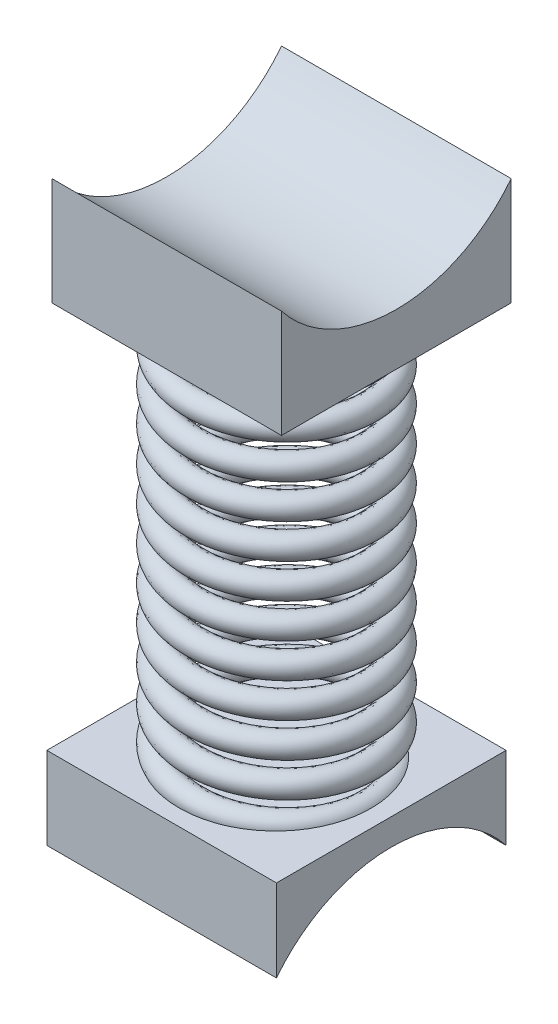
SolidWorks part; units mm, degrees
ref_plane "Front Plane" through (0, 0, 0) normal (0, 0, 1) x (1, 0, 0)
ref_plane "Top Plane" through (0, 0, 0) normal (0, 1, 0) x (1, 0, 0)
ref_plane "Right Plane" through (0, 0, 0) normal (1, 0, 0) x (0, 0, -1)
sketch "Sketch1" plane through (0, 0, 0) normal (0, 1, 0) x (1, 0, 0)
  circle A0 centre (0, 0) radius 7.62
curve "Helix/Spiral1" pitch 3 height 45 turns 15
sweep "Sweep1" add path "Helix/Spiral1" circular profile diameter 2 parameters "D3"=2
sketch "Sketch10" plane through (0, 0, 0) normal (0, 1, 0) x (1, 0, 0)
  line L1 (-10, 10) -> (10, 10)
  line L2 (-10, 10) -> (-10, -10)
  line L3 (-10, -10) -> (10, -10)
  line L4 (10, 10) -> (10, -10)
  line L5 (-10, 10) -> (10, -10) construction
  line L6 (-10, -10) -> (10, 10) construction
  point P0 (0, 0)
extrude "Boss-Extrude1" add sketch "Sketch10" along normal mid plane 10 contours L2 L1 L4 L3
sketch3d "3DSketch2"
  line L1 (-9.5584, 43.9677, -10) -> (10.4416, 43.9677, -10)
  line L2 (-9.5584, 43.9677, -10) -> (-9.5584, 43.9677, 10)
  line L3 (-9.5584, 43.9677, 10) -> (10.4416, 43.9677, 10)
  line L4 (10.4416, 43.9677, -10) -> (10.4416, 43.9677, 10)
  line L5 (-9.5584, 43.9677, -10) -> (10.4416, 43.9677, 10) construction
  line L6 (-9.5584, 43.9677, 10) -> (10.4416, 43.9677, -10) construction
  spline S0 degree 3 poles (-7.62, 0, 0) (-7.62, 0.0621, -0.9911) (-7.2232, 0.1877, -2.9949) (-5.5284, 0.375, -5.5277) (-2.992, 0.5625, -7.2234) (0, 0.75, -7.8183) (2.992, 0.9375, -7.2233) (5.5284, 1.125, -5.5284) (7.2232, 1.3125, -2.992) (7.8184, 1.5, 0) (7.2232, 1.6875, 2.992) (5.5284, 1.875, 5.5284) (2.992, 2.0625, 7.2232) (0, 2.25, 7.8184) (-2.992, 2.4375, 7.2232) (-5.5284, 2.625, 5.5284) (-7.2232, 2.8125, 2.992) (-7.8184, 3, 0) (-7.2232, 3.1875, -2.992) (-5.5284, 3.375, -5.5284) (-2.992, 3.5625, -7.2232) (0, 3.75, -7.8184) (2.992, 3.9375, -7.2232) (5.5284, 4.125, -5.5284) (7.2232, 4.3125, -2.992) (7.8184, 4.5, 0) (7.2232, 4.6875, 2.992) (5.5284, 4.875, 5.5284) (2.992, 5.0625, 7.2232) (0, 5.25, 7.8184) (-2.992, 5.4375, 7.2232) (-5.5284, 5.625, 5.5284) (-7.2232, 5.8125, 2.992) (-7.8184, 6, 0) (-7.2232, 6.1875, -2.992) (-5.5284, 6.375, -5.5284) (-2.992, 6.5625, -7.2232) (0, 6.75, -7.8184) (2.992, 6.9375, -7.2232) (5.5284, 7.125, -5.5284) (7.2232, 7.3125, -2.992) (7.8184, 7.5, 0) (7.2232, 7.6875, 2.992) (5.5284, 7.875, 5.5284) (2.992, 8.0625, 7.2232) (0, 8.25, 7.8184) (-2.992, 8.4375, 7.2232) (-5.5284, 8.625, 5.5284) (-7.2232, 8.8125, 2.992) (-7.8184, 9, 0) (-7.2232, 9.1875, -2.992) (-5.5284, 9.375, -5.5284) (-2.992, 9.5625, -7.2232) (0, 9.75, -7.8184) (2.992, 9.9375, -7.2232) (5.5284, 10.125, -5.5284) (7.2232, 10.3125, -2.992) (7.8184, 10.5, 0) (7.2232, 10.6875, 2.992) (5.5284, 10.875, 5.5284) (2.992, 11.0625, 7.2232) (0, 11.25, 7.8184) (-2.992, 11.4375, 7.2232) (-5.5284, 11.625, 5.5284) (-7.2232, 11.8125, 2.992) (-7.8184, 12, 0) (-7.2232, 12.1875, -2.992) (-5.5284, 12.375, -5.5284) (-2.992, 12.5625, -7.2232) (0, 12.75, -7.8184) (2.992, 12.9375, -7.2232) (5.5284, 13.125, -5.5284) (7.2232, 13.3125, -2.992) (7.8184, 13.5, 0) (7.2232, 13.6875, 2.992) (5.5284, 13.875, 5.5284) (2.992, 14.0625, 7.2232) (0, 14.25, 7.8184) (-2.992, 14.4375, 7.2232) (-5.5284, 14.625, 5.5284) (-7.2232, 14.8125, 2.992) (-7.8184, 15, 0) (-7.2232, 15.1875, -2.992) (-5.5284, 15.375, -5.5284) (-2.992, 15.5625, -7.2232) (0, 15.75, -7.8184) (2.992, 15.9375, -7.2232) (5.5284, 16.125, -5.5284) (7.2232, 16.3125, -2.992) (7.8184, 16.5, 0) (7.2232, 16.6875, 2.992) (5.5284, 16.875, 5.5284) (2.992, 17.0625, 7.2232) (0, 17.25, 7.8184) (-2.992, 17.4375, 7.2232) (-5.5284, 17.625, 5.5284) (-7.2232, 17.8125, 2.992) (-7.8184, 18, 0) (-7.2232, 18.1875, -2.992) (-5.5284, 18.375, -5.5284) (-2.992, 18.5625, -7.2232) (0, 18.75, -7.8184) (2.992, 18.9375, -7.2232) (5.5284, 19.125, -5.5284) (7.2232, 19.3125, -2.992) (7.8184, 19.5, 0) (7.2232, 19.6875, 2.992) (5.5284, 19.875, 5.5284) (2.992, 20.0625, 7.2232) (0, 20.25, 7.8184) (-2.992, 20.4375, 7.2232) (-5.5284, 20.625, 5.5284) (-7.2232, 20.8125, 2.992) (-7.8184, 21, 0) (-7.2232, 21.1875, -2.992) (-5.5284, 21.375, -5.5284) (-2.992, 21.5625, -7.2232) (0, 21.75, -7.8184) (2.992, 21.9375, -7.2232) (5.5284, 22.125, -5.5284) (7.2232, 22.3125, -2.992) (7.8184, 22.5, 0) (7.2232, 22.6875, 2.992) (5.5284, 22.875, 5.5284) (2.992, 23.0625, 7.2232) (0, 23.25, 7.8184) (-2.992, 23.4375, 7.2232) (-5.5284, 23.625, 5.5284) (-7.2232, 23.8125, 2.992) (-7.8184, 24, 0) (-7.2232, 24.1875, -2.992) (-5.5284, 24.375, -5.5284) (-2.992, 24.5625, -7.2232) (0, 24.75, -7.8184) (2.992, 24.9375, -7.2232) (5.5284, 25.125, -5.5284) (7.2232, 25.3125, -2.992) (7.8184, 25.5, 0) (7.2232, 25.6875, 2.992) (5.5284, 25.875, 5.5284) (2.992, 26.0625, 7.2232) (0, 26.25, 7.8184) (-2.992, 26.4375, 7.2232) (-5.5284, 26.625, 5.5284) (-7.2232, 26.8125, 2.992) (-7.8184, 27, 0) (-7.2232, 27.1875, -2.992) (-5.5284, 27.375, -5.5284) (-2.992, 27.5625, -7.2232) (0, 27.75, -7.8184) (2.992, 27.9375, -7.2232) (5.5284, 28.125, -5.5284) (7.2232, 28.3125, -2.992) (7.8184, 28.5, 0) (7.2232, 28.6875, 2.992) (5.5284, 28.875, 5.5284) (2.992, 29.0625, 7.2232) (0, 29.25, 7.8184) (-2.992, 29.4375, 7.2232) (-5.5284, 29.625, 5.5284) (-7.2232, 29.8125, 2.992) (-7.8184, 30, 0) (-7.2232, 30.1875, -2.992) (-5.5284, 30.375, -5.5284) (-2.992, 30.5625, -7.2232) (0, 30.75, -7.8184) (2.992, 30.9375, -7.2232) (5.5284, 31.125, -5.5284) (7.2232, 31.3125, -2.992) (7.8184, 31.5, 0) (7.2232, 31.6875, 2.992) (5.5284, 31.875, 5.5284) (2.992, 32.0625, 7.2232) (0, 32.25, 7.8184) (-2.992, 32.4375, 7.2232) (-5.5284, 32.625, 5.5284) (-7.2232, 32.8125, 2.992) (-7.8184, 33, 0) (-7.2232, 33.1875, -2.992) (-5.5284, 33.375, -5.5284) (-2.992, 33.5625, -7.2232) (0, 33.75, -7.8184) (2.992, 33.9375, -7.2232) (5.5284, 34.125, -5.5284) (7.2232, 34.3125, -2.992) (7.8184, 34.5, 0) (7.2232, 34.6875, 2.992) (5.5284, 34.875, 5.5284) (2.992, 35.0625, 7.2232) (0, 35.25, 7.8184) (-2.992, 35.4375, 7.2232) (-5.5284, 35.625, 5.5284) (-7.2232, 35.8125, 2.992) (-7.8184, 36, 0) (-7.2232, 36.1875, -2.992) (-5.5284, 36.375, -5.5284) (-2.992, 36.5625, -7.2232) (0, 36.75, -7.8184) (2.992, 36.9375, -7.2232) (5.5284, 37.125, -5.5284) (7.2232, 37.3125, -2.992) (7.8184, 37.5, 0) (7.2232, 37.6875, 2.992) (5.5284, 37.875, 5.5284) (2.992, 38.0625, 7.2232) (0, 38.25, 7.8184) (-2.992, 38.4375, 7.2232) (-5.5284, 38.625, 5.5284) (-7.2232, 38.8125, 2.992) (-7.8184, 39, 0) (-7.2232, 39.1875, -2.992) (-5.5284, 39.375, -5.5284) (-2.992, 39.5625, -7.2232) (0, 39.75, -7.8184) (2.992, 39.9375, -7.2232) (5.5284, 40.125, -5.5284) (7.2232, 40.3125, -2.992) (7.8184, 40.5, 0) (7.2232, 40.6875, 2.992) (5.5284, 40.875, 5.5284) (2.992, 41.0625, 7.2232) (0, 41.25, 7.8184) (-2.992, 41.4375, 7.2232) (-5.5284, 41.625, 5.5284) (-7.2232, 41.8125, 2.992) (-7.8184, 42, 0) (-7.2232, 42.1875, -2.992) (-5.5284, 42.375, -5.5284) (-2.992, 42.5625, -7.2232) (0, 42.75, -7.8184) (2.992, 42.9375, -7.2232) (5.5284, 43.125, -5.5284) (7.2232, 43.3125, -2.992) (7.8184, 43.5, 0) (7.2232, 43.6875, 2.992) (5.5284, 43.875, 5.5284) (2.992, 44.0625, 7.2233) (0, 44.25, 7.8183) (-2.992, 44.4375, 7.2234) (-5.5284, 44.625, 5.5277) (-7.2232, 44.8123, 2.9949) (-7.62, 44.9379, 0.9911) (-7.62, 45, 0) knots 0 0 0 0 0.004167 0.008333 0.0125 0.016667 0.020833 0.025 0.029167 0.033333 0.0375 0.041667 0.045833 0.05 0.054167 0.058333 0.0625 0.066667 0.070833 0.075 0.079167 0.083333 0.0875 0.091667 0.095833 0.1 0.104167 0.108333 0.1125 0.116667 0.120833 0.125 0.129167 0.133333 0.1375 0.141667 0.145833 0.15 0.154167 0.158333 0.1625 0.166667 0.170833 0.175 0.179167 0.183333 0.1875 0.191667 0.195833 0.2 0.204167 0.208333 0.2125 0.216667 0.220833 0.225 0.229167 0.233333 0.2375 0.241667 0.245833 0.25 0.254167 0.258333 0.2625 0.266667 0.270833 0.275 0.279167 0.283333 0.2875 0.291667 0.295833 0.3 0.304167 0.308333 0.3125 0.316667 0.320833 0.325 0.329167 0.333333 0.3375 0.341667 0.345833 0.35 0.354167 0.358333 0.3625 0.366667 0.370833 0.375 0.379167 0.383333 0.3875 0.391667 0.395833 0.4 0.404167 0.408333 0.4125 0.416667 0.420833 0.425 0.429167 0.433333 0.4375 0.441667 0.445833 0.45 0.454167 0.458333 0.4625 0.466667 0.470833 0.475 0.479167 0.483333 0.4875 0.491667 0.495833 0.5 0.504167 0.508333 0.5125 0.516667 0.520833 0.525 0.529167 0.533333 0.5375 0.541667 0.545833 0.55 0.554167 0.558333 0.5625 0.566667 0.570833 0.575 0.579167 0.583333 0.5875 0.591667 0.595833 0.6 0.604167 0.608333 0.6125 0.616667 0.620833 0.625 0.629167 0.633333 0.6375 0.641667 0.645833 0.65 0.654167 0.658333 0.6625 0.666667 0.670833 0.675 0.679167 0.683333 0.6875 0.691667 0.695833 0.7 0.704167 0.708333 0.7125 0.716667 0.720833 0.725 0.729167 0.733333 0.7375 0.741667 0.745833 0.75 0.754167 0.758333 0.7625 0.766667 0.770833 0.775 0.779167 0.783333 0.7875 0.791667 0.795833 0.8 0.804167 0.808333 0.8125 0.816667 0.820833 0.825 0.829167 0.833333 0.8375 0.841667 0.845833 0.85 0.854167 0.858333 0.8625 0.866667 0.870833 0.875 0.879167 0.883333 0.8875 0.891667 0.895833 0.9 0.904167 0.908333 0.9125 0.916667 0.920833 0.925 0.929167 0.933333 0.9375 0.941667 0.945833 0.95 0.954167 0.958333 0.9625 0.966667 0.970833 0.975 0.979167 0.983333 0.9875 0.991667 0.995833 1 1 1 1 construction
  point P0 (6.4461, 43.2315, -4.0626)
extrude "Boss-Extrude2" add sketch "3DSketch2" along direction (0, -1, 0) on the side of the normal mid plane 10 contours L2 L1 L4 L3
sketch "Sketch11" plane through (10, 0, 0) normal (1, 0, 0) x (0, 0, -1)
  circle A0 centre (0, -10) radius 12.7
  circle A1 centre (0, -10) radius 1.27
extrude "Cut-Extrude1" cut sketch "Sketch11" against normal blind 20
sketch "Sketch12" plane through (10.4416, 0, 0) normal (1, 0, 0) x (0, 0, -1)
  circle A0 centre (0, 56.1749) radius 12.7
  point P2 (0, 21.2147)
  point P3 (0, 41.7564)
  point P4 (0, 56.1749)
extrude "Cut-Extrude2" cut sketch "Sketch12" against normal blind 20
